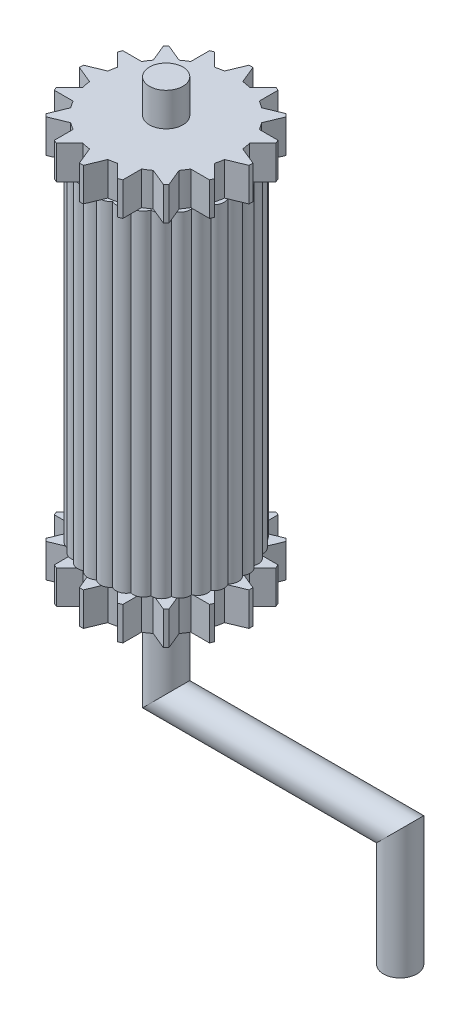
SolidWorks part; units mm, degrees
ref_plane "Front Plane" through (0, 0, 0) normal (1, 0, 0) x (0, 1, 0)
ref_plane "Top Plane" through (0, 0, 0) normal (0, 0, 1) x (0, 1, 0)
ref_plane "Right Plane" through (0, 0, 0) normal (0, 1, 0) x (-1, 0, 0)
sketch "Sketch2" plane through (0, 0, 0) normal (0, 1, 0) x (-1, 0, 0)
  arc A83 (20.6915, 2.1748) -> (20.6915, -2.1748) centre (18.625, 0) cw
  arc A84 (20.6915, -2.1748) -> (19.7872, -6.4292) centre (18.218, -3.8724) cw
  arc A85 (19.7872, -6.4292) -> (18.0181, -10.4027) centre (17.0148, -7.5755) cw
  arc A86 (18.0181, -10.4027) -> (15.4615, -13.9216) centre (15.0679, -10.9475) cw
  arc A87 (15.4615, -13.9216) -> (12.2291, -16.832) centre (12.4626, -13.8411) cw
  arc A88 (12.2291, -16.832) -> (8.4623, -19.0067) centre (9.3125, -16.1297) cw
  arc A89 (8.4623, -19.0067) -> (4.3257, -20.3508) centre (5.7554, -17.7134) cw
  arc A90 (4.3257, -20.3508) -> (0, -20.8055) centre (1.9468, -18.523) cw
  arc A91 (0, -20.8055) -> (-4.3257, -20.3508) centre (-1.9468, -18.523) cw
  arc A92 (-4.3257, -20.3508) -> (-8.4623, -19.0067) centre (-5.7554, -17.7134) cw
  arc A93 (-8.4623, -19.0067) -> (-12.2291, -16.832) centre (-9.3125, -16.1297) cw
  arc A94 (-12.2291, -16.832) -> (-15.4615, -13.9216) centre (-12.4626, -13.8411) cw
  arc A95 (-15.4615, -13.9216) -> (-18.0181, -10.4027) centre (-15.0679, -10.9475) cw
  arc A96 (-18.0181, -10.4027) -> (-19.7872, -6.4292) centre (-17.0148, -7.5755) cw
  arc A97 (-19.7872, -6.4292) -> (-20.6915, -2.1748) centre (-18.218, -3.8724) cw
  arc A98 (-20.6915, -2.1748) -> (-20.6915, 2.1748) centre (-18.625, 0) cw
  arc A99 (-20.6915, 2.1748) -> (-19.7872, 6.4292) centre (-18.218, 3.8724) cw
  arc A100 (-19.7872, 6.4292) -> (-18.0181, 10.4027) centre (-17.0148, 7.5755) cw
  arc A101 (-18.0181, 10.4027) -> (-15.4615, 13.9216) centre (-15.0679, 10.9475) cw
  arc A102 (-15.4615, 13.9216) -> (-12.2291, 16.832) centre (-12.4626, 13.8411) cw
  arc A103 (-12.2291, 16.832) -> (-8.4623, 19.0067) centre (-9.3125, 16.1297) cw
  arc A104 (-8.4623, 19.0067) -> (-4.3257, 20.3508) centre (-5.7554, 17.7134) cw
  arc A105 (-4.3257, 20.3508) -> (0, 20.8055) centre (-1.9468, 18.523) cw
  arc A106 (0, 20.8055) -> (4.3257, 20.3508) centre (1.9468, 18.523) cw
  arc A107 (4.3257, 20.3508) -> (8.4623, 19.0067) centre (5.7554, 17.7134) cw
  arc A108 (8.4623, 19.0067) -> (12.2291, 16.832) centre (9.3125, 16.1297) cw
  arc A109 (12.2291, 16.832) -> (15.4615, 13.9216) centre (12.4626, 13.8411) cw
  arc A110 (15.4615, 13.9216) -> (18.0181, 10.4027) centre (15.0679, 10.9475) cw
  arc A111 (18.0181, 10.4027) -> (19.7872, 6.4292) centre (17.0148, 7.5755) cw
  arc A112 (19.7872, 6.4292) -> (20.6915, 2.1748) centre (18.218, 3.8724) cw
  point P0 (0, 0)
  point P31 (0, 0)
  point P62 (0, 0)
  dimension "D1" = 3
extrude "Boss-Extrude2" add sketch "Sketch2" along normal blind 100
sketch "Sketch3" plane through (0, 0, 0) normal (0, -1, 0) x (1, 0, 0)
  line L0 (0, -57.0817) -> (0, 57.0817) construction
  line L1 (0, 25.375) -> (2.1167, 20.2647) construction
  line L2 (0, 25.375) -> (-2.1167, 20.2647) construction
  line L5 (-2.733, 20.1909) -> (2.733, 20.1909) construction
  line L32 (-2.733, 20.1909) -> (-0.5885, 25.3682)
  line L33 (2.733, 20.1909) -> (0.5885, 25.3682)
  line L34 (5.2017, 19.6998) -> (9.1643, 23.6623)
  line L35 (10.2517, 17.6081) -> (10.2517, 23.2119)
  line L36 (12.3446, 16.2096) -> (17.5219, 18.3541)
  line L37 (16.2096, 12.3446) -> (18.3541, 17.5219)
  line L38 (17.6081, 10.2517) -> (23.2119, 10.2517)
  line L39 (19.6998, 5.2017) -> (23.6623, 9.1643)
  line L40 (20.1909, 2.733) -> (25.3682, 0.5885)
  line L41 (20.1909, -2.733) -> (25.3682, -0.5885)
  line L42 (19.6998, -5.2017) -> (23.6623, -9.1643)
  line L43 (17.6081, -10.2517) -> (23.2119, -10.2517)
  line L44 (16.2096, -12.3446) -> (18.3541, -17.5219)
  line L45 (12.3446, -16.2096) -> (17.5219, -18.3541)
  line L46 (10.2517, -17.6081) -> (10.2517, -23.2119)
  line L47 (5.2017, -19.6998) -> (9.1643, -23.6623)
  line L48 (2.733, -20.1909) -> (0.5885, -25.3682)
  line L49 (-2.733, -20.1909) -> (-0.5885, -25.3682)
  line L50 (-5.2017, -19.6998) -> (-9.1643, -23.6623)
  line L51 (-10.2517, -17.6081) -> (-10.2517, -23.2119)
  line L52 (-12.3446, -16.2096) -> (-17.5219, -18.3541)
  line L53 (-16.2096, -12.3446) -> (-18.3541, -17.5219)
  line L54 (-17.6081, -10.2517) -> (-23.2119, -10.2517)
  line L55 (-19.6998, -5.2017) -> (-23.6623, -9.1643)
  line L56 (-20.1909, -2.733) -> (-25.3682, -0.5885)
  line L57 (-20.1909, 2.733) -> (-25.3682, 0.5885)
  line L58 (-19.6998, 5.2017) -> (-23.6623, 9.1643)
  line L59 (-17.6081, 10.2517) -> (-23.2119, 10.2517)
  line L60 (-16.2096, 12.3446) -> (-18.3541, 17.5219)
  line L61 (-12.3446, 16.2096) -> (-17.5219, 18.3541)
  line L62 (-10.2517, 17.6081) -> (-10.2517, 23.2119)
  line L63 (-5.2017, 19.6998) -> (-9.1643, 23.6623)
  arc A28 (-16.2096, 12.3446) -> (-17.6081, 10.2517) centre (0, 0) ccw
  arc A29 (-23.2119, 10.2517) -> (-23.6623, 9.1643) centre (0, 0) ccw
  arc A30 (-17.5219, 18.3541) -> (-18.3541, 17.5219) centre (0, 0) ccw
  arc A31 (-10.2517, 17.6081) -> (-12.3446, 16.2096) centre (0, 0) ccw
  arc A32 (-9.1643, 23.6623) -> (-10.2517, 23.2119) centre (0, 0) ccw
  arc A33 (0.5885, 25.3682) -> (-0.5885, 25.3682) centre (0, 0) ccw
  arc A34 (10.2517, 23.2119) -> (9.1643, 23.6623) centre (0, 0) ccw
  arc A35 (-2.733, 20.1909) -> (-5.2017, 19.6998) centre (0, 0) ccw
  arc A36 (5.2017, 19.6998) -> (2.733, 20.1909) centre (0, 0) ccw
  arc A37 (18.3541, 17.5219) -> (17.5219, 18.3541) centre (0, 0) ccw
  arc A38 (12.3446, 16.2096) -> (10.2517, 17.6081) centre (0, 0) ccw
  arc A39 (17.6081, 10.2517) -> (16.2096, 12.3446) centre (0, 0) ccw
  arc A40 (23.6623, 9.1643) -> (23.2119, 10.2517) centre (0, 0) ccw
  arc A41 (25.3682, -0.5885) -> (25.3682, 0.5885) centre (0, 0) ccw
  arc A42 (23.2119, -10.2517) -> (23.6623, -9.1643) centre (0, 0) ccw
  arc A43 (20.1909, 2.733) -> (19.6998, 5.2017) centre (0, 0) ccw
  arc A44 (19.6998, -5.2017) -> (20.1909, -2.733) centre (0, 0) ccw
  arc A45 (17.5219, -18.3541) -> (18.3541, -17.5219) centre (0, 0) ccw
  arc A46 (9.1643, -23.6623) -> (10.2517, -23.2119) centre (0, 0) ccw
  arc A47 (10.2517, -17.6081) -> (12.3446, -16.2096) centre (0, 0) ccw
  arc A48 (16.2096, -12.3446) -> (17.6081, -10.2517) centre (0, 0) ccw
  arc A49 (-0.5885, -25.3682) -> (0.5885, -25.3682) centre (0, 0) ccw
  arc A50 (-10.2517, -23.2119) -> (-9.1643, -23.6623) centre (0, 0) ccw
  arc A51 (-5.2017, -19.6998) -> (-2.733, -20.1909) centre (0, 0) ccw
  arc A52 (2.733, -20.1909) -> (5.2017, -19.6998) centre (0, 0) ccw
  arc A53 (-18.3541, -17.5219) -> (-17.5219, -18.3541) centre (0, 0) ccw
  arc A54 (-23.6623, -9.1643) -> (-23.2119, -10.2517) centre (0, 0) ccw
  arc A55 (-12.3446, -16.2096) -> (-10.2517, -17.6081) centre (0, 0) ccw
  arc A56 (-17.6081, -10.2517) -> (-16.2096, -12.3446) centre (0, 0) ccw
  arc A57 (-20.1909, -2.733) -> (-19.6998, -5.2017) centre (0, 0) ccw
  arc A58 (-25.3682, 0.5885) -> (-25.3682, -0.5885) centre (0, 0) ccw
  arc A59 (-19.6998, 5.2017) -> (-20.1909, 2.733) centre (0, 0) ccw
  point P13 (0, 57.0817)
  point P17 (0, 47.4976)
  point P78 (0, 0)
  dimension "D2" = 50.75
  dimension "D1" = 40.75
  dimension "D3" = 22.5
  dimension "D4" = 22.5
  dimension "D5" = 5.466
  dimension "D6" = 16
extrude "Boss-Extrude3" add sketch "Sketch3" along normal blind 10
ref_plane "Plane1" through (0, 50, 0) normal (0, 1, 0) x (1, 0, 0)
mirror "Mirror1" about plane through (0, 50, 0) normal (0, 1, 0) of "Boss-Extrude3"
sketch "Sketch4" plane through (0, -10, 0) normal (0, -1, 0) x (1, 0, 0)
  circle A0 centre (0, 0) radius 5
  dimension "D1" = 10
extrude "Boss-Extrude4" add sketch "Sketch4" along normal blind 10
mirror "Mirror2" about plane through (0, 50, 0) normal (0, 1, 0) of "Boss-Extrude4"
sketch "Sketch6" plane through (0, 0, 0) normal (0, 0, 1) x (0, 1, 0)
  line L0 (-20, 0) -> (-40, 0)
  line L1 (-20, 5) -> (-20, -5) construction
  line L2 (-40, 0) -> (-40, -70)
  line L3 (-40, -70) -> (-75, -70)
  dimension "D1" = 20
  dimension "D2" = 70
  dimension "D3" = 35
sweep "Sweep1" add path "Sketch6" circular profile diameter 10 parameters "D3"=10
